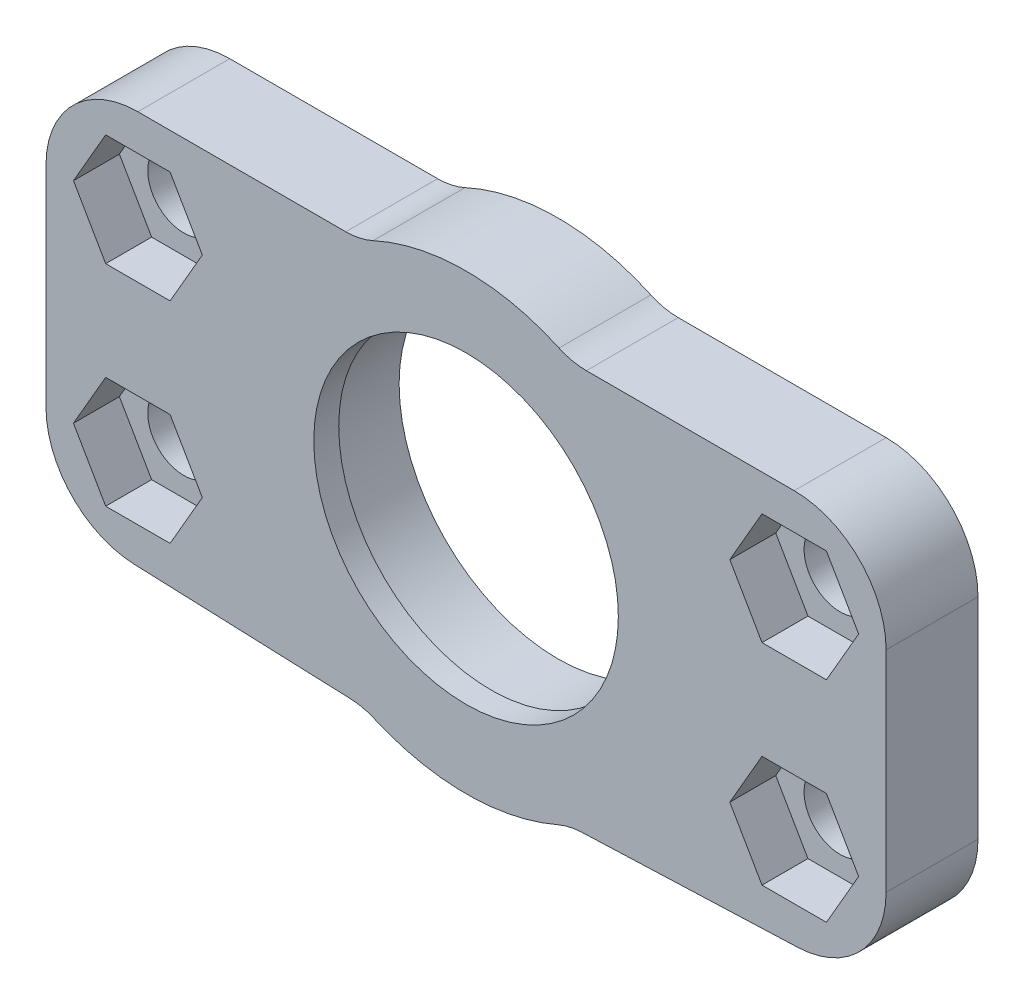
SolidWorks part; units mm, degrees
ref_plane "Front Plane" through (0, 0, 0) normal (0, 0, 1) x (1, 0, 0)
ref_plane "Top Plane" through (0, 0, 0) normal (0, 1, 0) x (1, 0, 0)
ref_plane "Right Plane" through (0, 0, 0) normal (1, 0, 0) x (0, 0, -1)
sketch "Sketch1" plane through (0, 0, 0) normal (0, 0, 1) x (1, 0, 0)
  line L0 (24, 32.5) -> (7, 32.5)
  line L1 (0, 25.5) -> (0, 9.5)
  line L2 (7, 25.5) -> (7, 9.5) construction
  line L3 (24.2008, 1.834) -> (6.7313, 2.5052)
  line L5 (32, 34.5) -> (32, 29.1)
  line L6 (32, 5.9) -> (32, 0)
  arc A0 (32, 29.1) -> (32, 5.9) centre (32, 17.5) ccw
  arc A1 (32, 34.5) -> (24, 32.5) centre (32, 17.5) ccw
  arc A2 (24.2008, 1.834) -> (32, 0) centre (32, 17.5) ccw
  circle A3 centre (7, 25.5) radius 2.75
  arc A4 (7, 32.5) -> (0, 25.5) centre (7, 25.5) ccw
  circle A5 centre (7, 9.5) radius 2.75
  arc A6 (0, 9.5) -> (6.7313, 2.5052) centre (7, 9.5) ccw
  dimension "D2" = 11.6
  dimension "D3" = 17
  dimension "D4" = 17.5
  dimension "D5" = 7
  dimension "D6" = 5.5
  dimension "D1" = 16
  dimension "D7" = 25
  dimension "D8" = 8
  dimension "D9" = 92.2
extrude "Boss-Extrude1" add sketch "Sketch1" along normal blind 7 separate body
sketch "Sketch2" plane through (0, 0, 0) normal (0, 0, -1) x (-1, 0, 0)
  circle A0 centre (-32, 17.5) radius 12.1
  dimension "D1" = 24.2
extrude "Cut-Extrude1" cut sketch "Sketch2" against normal blind 5.1
sketch "Sketch3" plane through (0, 0, 7) normal (0, 0, 1) x (1, 0, 0)
  line L1 (4.5463, 29.75) -> (2.0925, 25.5)
  line L2 (2.0925, 25.5) -> (4.5463, 21.25)
  line L3 (4.5463, 21.25) -> (9.4537, 21.25)
  line L4 (9.4537, 21.25) -> (11.9075, 25.5)
  line L5 (11.9075, 25.5) -> (9.4537, 29.75)
  line L6 (9.4537, 29.75) -> (4.5463, 29.75)
  line L7 (4.5463, 13.75) -> (2.0925, 9.5)
  line L8 (2.0925, 9.5) -> (4.5463, 5.25)
  line L9 (4.5463, 5.25) -> (9.4537, 5.25)
  line L10 (9.4537, 5.25) -> (11.9075, 9.5)
  line L11 (11.9075, 9.5) -> (9.4537, 13.75)
  line L12 (9.4537, 13.75) -> (4.5463, 13.75)
  circle A0 centre (7, 25.5) radius 4.25 construction
  circle A1 centre (7, 9.5) radius 4.25 construction
  dimension "D1" = 8.5
extrude "Cut-Extrude2" cut sketch "Sketch3" against normal blind 3.5
fillet "Fillet1" radius 5 2 edges at (24.2008, 1.834, 3.5) (24, 32.5, 3.5)
mirror "Mirror1" about plane through (32, 34.5, 7) normal (-1, 0, 0) of bodies 104
